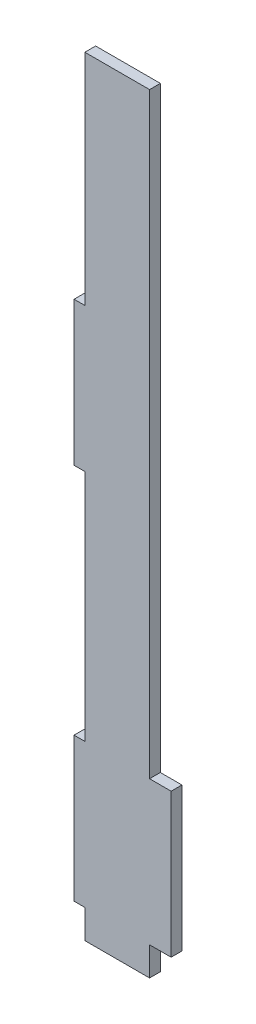
SolidWorks part; units mm, degrees
ref_plane "Front Plane" through (0, 0, 0) normal (0, 0, 1) x (1, 0, 0)
ref_plane "Top Plane" through (0, 0, 0) normal (0, 1, 0) x (1, 0, 0)
ref_plane "Right Plane" through (0, 0, 0) normal (1, 0, 0) x (0, 0, -1)
sketch "Sketch1" plane through (0, 0, 0) normal (0, 0, 1) x (1, 0, 0)
  line L1 (-18, 61) -> (0, 61)
  line L2 (-18, 61) -> (-18, 0)
  line L3 (-18, 0) -> (0, 0)
  line L4 (0, 61) -> (0, 0)
  dimension "D1" = 61
  dimension "D2" = 18
extrude "Base Shape" add sketch "Sketch1" along normal blind 3
sketch "Sketch2" plane through (0, 0, 3) normal (0, 0, 1) x (1, 0, 0)
  line L0 (-18, 61) -> (-18, 0) construction
  line L1 (-18, 8) -> (-21, 8)
  line L2 (-18, 8) -> (-18, 48)
  line L3 (-18, 48) -> (-21, 48)
  line L4 (-21, 8) -> (-21, 48)
  line L5 (0, 0) -> (0, 61) construction
  line L6 (0, 8) -> (6, 8)
  line L7 (0, 8) -> (0, 48)
  line L8 (0, 48) -> (6, 48)
  line L9 (6, 8) -> (6, 48)
  line L10 (-18, 0) -> (0, 0) construction
  line M11 (0, 0) -> (0, 61)
  dimension "D1" = 8
  dimension "D2" = 40
  dimension "D3" = 3
  dimension "D4" = 6
extrude "Fingers" add sketch "Sketch2" against normal up to surface (3 mm away) contours L6 L9 L8 M11 | L4 L3 L2 L1 up to face at (-9, 30.5, 0)
sketch "Sketch3" plane through (0, 61, 0) normal (0, 1, 0) x (1, 0, 0)
  line L1 (-18, 0) -> (0, 0)
  line L2 (-18, 0) -> (-18, -3)
  line L3 (-18, -3) -> (0, -3)
  line L4 (0, 0) -> (0, -3)
extrude "Boss-Extrude1" add sketch "Sketch3" along normal blind 153
sketch "Sketch4" plane through (0, 0, 3) normal (0, 0, 1) x (1, 0, 0)
  line L0 (-18, 214) -> (-18, 48) construction
  line L1 (-18, 113) -> (-21, 113)
  line L2 (-18, 113) -> (-18, 153)
  line L3 (-18, 153) -> (-21, 153)
  line L4 (-21, 113) -> (-21, 153)
  line L5 (-21, 8) -> (-21, 48) construction
  line L6 (-18, 48) -> (-21, 48) construction
  dimension "D1" = 65
extrude "Boss-Extrude3" add sketch "Sketch4" against normal through all
